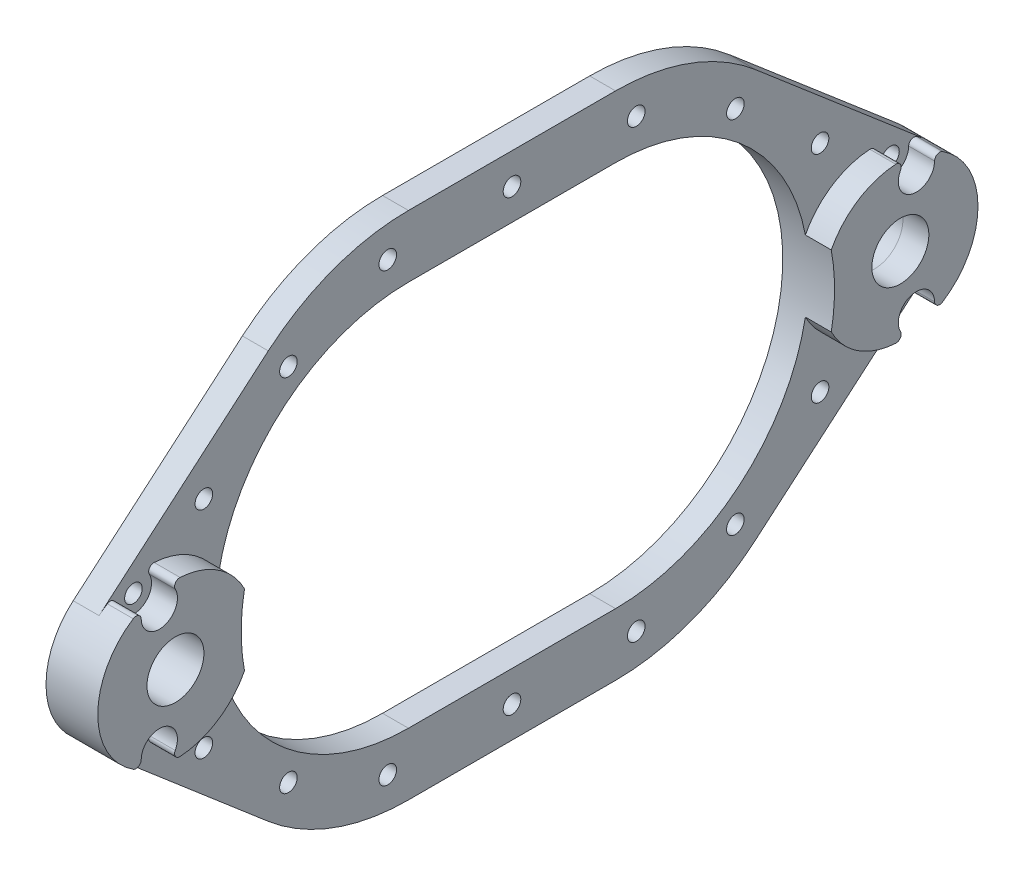
SolidWorks part; units mm, degrees
ref_plane "Front Plane" through (0, 0, 0) normal (0, 0, 1) x (1, 0, 0)
ref_plane "Top Plane" through (0, 0, 0) normal (0, 1, 0) x (1, 0, 0)
ref_plane "Right Plane" through (0, 0, 0) normal (1, 0, 0) x (0, 0, -1)
sketch "Sketch1" plane through (0, 0, 0) normal (1, 0, 0) x (0, 0, -1)
  line L0 (-25.4, 62.611) -> (25.4, 62.611)
  line L1 (-107.95, -62.611) -> (107.95, -62.611) construction
  line L2 (-107.95, -62.611) -> (-107.95, 62.611) construction
  line L3 (-107.95, 62.611) -> (107.95, 62.611) construction
  line L4 (107.95, -62.611) -> (107.95, 62.611) construction
  line L5 (-107.95, -62.611) -> (107.95, 62.611) construction
  line L6 (-107.95, 62.611) -> (107.95, -62.611) construction
  line L7 (-101.281, 14.478) -> (-59.7774, 49.9703)
  line L8 (-101.281, -14.478) -> (-59.7774, -49.9703)
  line L9 (-25.4, -62.611) -> (25.4, -62.611)
  line L10 (101.2694, 14.4879) -> (59.7372, 49.9468)
  line L11 (101.2694, -14.488) -> (59.7372, -49.9468)
  circle A0 centre (88.9, 0) radius 19.05
  circle A1 centre (-88.9, 0) radius 19.05
  arc A2 (-25.4, 62.611) -> (-59.7774, 49.9703) centre (-25.4, 9.5445) ccw
  arc A3 (-25.4, -62.611) -> (-59.7774, -49.9703) centre (-25.4, -9.5445) cw
  arc A4 (25.4, 62.611) -> (59.7372, 49.9468) centre (25.4, 9.7285) cw
  arc A5 (25.4, -62.611) -> (59.7372, -49.9468) centre (25.4, -9.7285) ccw
  point P0 (0, 0)
  point P13 (0, 62.611)
  point P21 (0, -62.611)
  dimension "D3" = 38.1
  dimension "D1" = 125.222
  dimension "D2" = 215.9
  dimension "D4" = 50.8
  dimension "D5" = 14.478
  dimension "D6" = 54.61
  dimension "D7" = 88.9
  dimension "D8" = 88.9
  dimension "D9" = 14.478
  dimension "D10" = 54.61
extrude "Boss-Extrude1" add sketch "Sketch1" along normal blind 6.35 contours L9 A5 L11 A0 L10 A4 L0 A2 L7 A1 L8 A3 | A0 | A1
sketch "Sketch3" plane through (6.35, 0, 0) normal (1, 0, 0) x (0, 0, -1)
  line L0 (-107.95, 0) -> (107.95, 0) construction
  circle A0 centre (-88.9, 0) radius 6.985
  circle A1 centre (88.9, 0) radius 6.985
  arc A2 (-101.281, 14.478) -> (-101.281, -14.478) centre (-88.9, 0) ccw construction
  arc A3 (101.2694, -14.488) -> (101.2694, 14.4879) centre (88.9, 0) ccw construction
  point P6 (0, 0)
  dimension "D1" = 13.97
  dimension "D2" = 13.97
  dimension "D3" = 19.05
  dimension "D4" = 19.05
extrude "Cut-Extrude2" cut sketch "Sketch3" against normal blind 6.35
sketch "Sketch2" plane through (6.35, 0, 0) normal (1, 0, 0) x (0, 0, -1)
  line L0 (-25.4, 0) -> (25.4, 0) construction
  line L3 (-25.4, 47.371) -> (25.4, 47.371)
  line L4 (-25.4, 47.371) -> (25.4, 47.371)
  line L6 (-25.4, -47.371) -> (25.4, -47.371)
  line L7 (-25.4, -47.371) -> (25.4, -47.371)
  arc A4 (-25.4, 47.371) -> (-25.4, -47.371) centre (-25.4, 0) ccw
  arc A5 (25.4, -47.371) -> (25.4, 47.371) centre (25.4, 0) ccw
  point P3 (0, 0)
  point P4 (0, -47.371)
  point P11 (0, 0)
  dimension "D2" = 15.24
  dimension "D3" = 15.24
extrude "Cut-Extrude1" cut sketch "Sketch2" against normal blind 6.35
sketch "Sketch4" plane through (6.35, 0, 0) normal (1, 0, 0) x (0, 0, -1)
  line L0 (-131.1141, 0) -> (130.289, 0) construction
  line L12 (-25.4, -54.991) -> (25.4, -54.991)
  line L13 (54.7895, -44.1517) -> (96.3216, -8.6928)
  line L14 (96.3216, 8.6928) -> (54.7895, 44.1517)
  line L15 (25.4, 54.991) -> (-25.4, 54.991)
  line L16 (-54.8333, 44.172) -> (-96.3286, 8.6868)
  line L17 (-96.3286, -8.6868) -> (-54.8333, -44.172)
  line L18 (-25.4, -54.991) -> (25.4, -54.991)
  line L19 (54.7895, -44.1517) -> (96.3216, -8.6928)
  line L20 (96.3216, 8.6928) -> (54.7895, 44.1517)
  line L21 (25.4, 54.991) -> (-25.4, 54.991)
  line L22 (-54.8333, 44.172) -> (-96.3286, 8.6868)
  line L23 (-96.3286, -8.6868) -> (-54.8333, -44.172)
  circle A0 centre (-30.48, 54.7062) radius 2.159
  circle A1 centre (-54.8333, 44.172) radius 2.159
  circle A2 centre (54.7895, 44.1517) radius 2.159
  circle A3 centre (30.4787, 54.7052) radius 2.159
  circle A4 centre (-75.581, 26.4294) radius 2.159
  circle A5 centre (75.5556, 26.4222) radius 2.159
  circle A8 centre (0, 54.991) radius 2.159
  circle A11 centre (-92.853, 14.9994) radius 2.159
  arc A12 (25.4, -54.991) -> (54.7895, -44.1517) centre (25.4, -9.7285) ccw
  arc A13 (96.3216, -8.6928) -> (96.3216, 8.6928) centre (88.9, 0) ccw
  arc A14 (54.7895, 44.1517) -> (25.4, 54.991) centre (25.4, 9.7285) ccw
  arc A15 (-25.4, 54.991) -> (-54.8333, 44.172) centre (-25.4, 9.5445) ccw
  arc A16 (-96.3286, 8.6868) -> (-96.3286, -8.6868) centre (-88.9, 0) ccw
  arc A17 (-54.8333, -44.172) -> (-25.4, -54.991) centre (-25.4, -9.5445) ccw
  arc A18 (25.4, -54.991) -> (54.7895, -44.1517) centre (25.4, -9.7285) ccw
  arc A19 (96.3216, -8.6928) -> (96.3216, 8.6928) centre (88.9, 0) ccw
  arc A20 (54.7895, 44.1517) -> (25.4, 54.991) centre (25.4, 9.7285) ccw
  arc A21 (-25.4, 54.991) -> (-54.8333, 44.172) centre (-25.4, 9.5445) ccw
  arc A22 (-96.3286, 8.6868) -> (-96.3286, -8.6868) centre (-88.9, 0) ccw
  arc A23 (-54.8333, -44.172) -> (-25.4, -54.991) centre (-25.4, -9.5445) ccw
  circle A24 centre (92.8276, 14.9922) radius 2.159
  circle A25 centre (92.8276, -14.9922) radius 2.159
  circle A26 centre (75.5556, -26.4222) radius 2.159
  circle A27 centre (54.7895, -44.1517) radius 2.159
  circle A28 centre (30.4787, -54.7052) radius 2.159
  circle A29 centre (0, -54.991) radius 2.159
  circle A30 centre (-30.48, -54.7062) radius 2.159
  circle A31 centre (-54.8333, -44.172) radius 2.159
  circle A32 centre (-75.581, -26.4294) radius 2.159
  circle A33 centre (-92.853, -14.9994) radius 2.159
  dimension "D2" = 4.318
  dimension "D5" = 4.318
  dimension "D6" = 4.318
  dimension "D9" = 4.318
  dimension "D3" = 30.48
  dimension "D4" = 30.48
  dimension "D7" = 11.43
  dimension "D8" = 17.272
  dimension "D10" = 17.272
  dimension "D11" = 11.43
  dimension "D1" = 7.62
extrude "Cut-Extrude3" cut sketch "Sketch4" against normal through all both and the other way through all contours L22 A4 | A1 | A0 | A8 | A3 | A2 | A5 | A24 | A25 | A26 | A27 | A28 | A29 | A30 | A31 | A32 | A11 | A33
sketch "Sketch6" plane through (6.35, 0, 0) normal (1, 0, 0) x (0, 0, -1)
  arc A0 (-71.9619, 8.718) -> (-87.7671, 19.0163) centre (-88.9, 0) ccw
  arc A2 (-97.2976, 14.9393) -> (-88.9561, 17.1376) centre (-92.853, 14.9994) ccw
  arc A5 (-88.9561, -17.1376) -> (-97.2976, -14.9393) centre (-92.853, -14.9994) ccw
  arc A6 (-99.258, 15.9879) -> (-99.258, -15.9879) centre (-88.9, 0) ccw
  arc A7 (-87.7671, -19.0163) -> (-71.9619, -8.718) centre (-88.9, 0) ccw
  arc A8 (-97.2976, -14.9393) -> (-99.258, -15.9879) centre (-98.5675, -14.9221) cw
  arc A9 (-88.9561, 17.1376) -> (-87.7671, 19.0163) centre (-87.8426, 17.7485) cw
  arc A10 (-97.2976, 14.9393) -> (-99.258, 15.9879) centre (-98.5675, 14.9221) ccw
  arc A11 (-88.9561, -17.1376) -> (-87.7671, -19.0163) centre (-87.8426, -17.7485) ccw
  circle A12 centre (-88.9, 0) radius 6.985
  arc A15 (-25.4, 47.371) -> (-25.4, -47.371) centre (-25.4, 0) ccw
  arc A16 (-71.9619, 8.718) -> (-71.9619, -8.718) centre (-25.4, 0) ccw
  point P9 (0, 0)
  point P10 (0, 0)
  point P21 (-96.5693, 17.438)
  point P24 (-90.8212, -18.9529)
  dimension "D2" = 8.89
  dimension "D3" = 8.89
  dimension "D4" = 19.05
  dimension "D5" = 1.27
  dimension "D6" = 1.27
  dimension "D7" = 13.97
  dimension "D1" = 0
extrude "Boss-Extrude2" add sketch "Sketch6" along normal blind 6.35
mirror "Mirror1" about plane through (0, 0, 0) normal (0, 0, 1) of "Boss-Extrude2"
